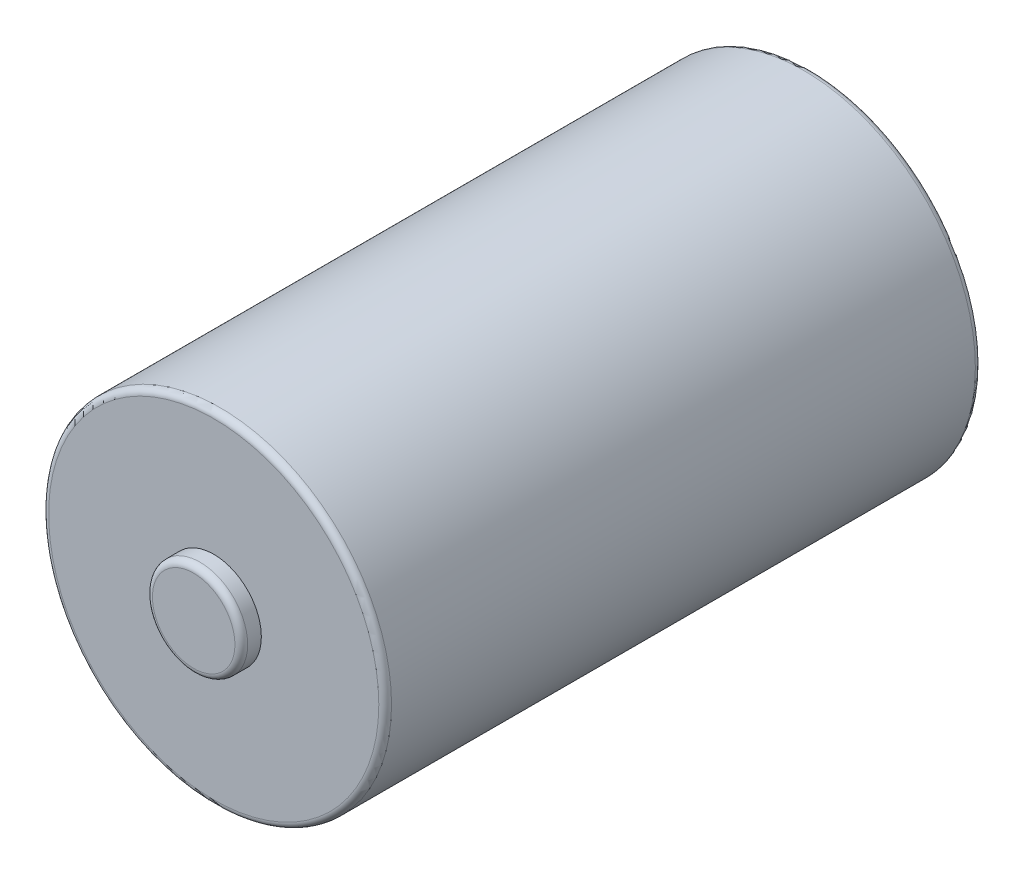
SolidWorks part; units mm, degrees
ref_plane "Front Plane" through (0, 0, 0) normal (0, 0, 1) x (1, 0, 0)
ref_plane "Top Plane" through (0, 0, 0) normal (0, 1, 0) x (1, 0, 0)
ref_plane "Right Plane" through (0, 0, 0) normal (1, 0, 0) x (0, 0, -1)
sketch "Sketch1" plane through (0, 0, 0) normal (0, 0, 1) x (1, 0, 0)
  circle A0 centre (0, 0) radius 17.1
extrude "Boss-Extrude1" add sketch "Sketch1" along normal blind 59.5
sketch "Sketch2" plane through (0, 0, 59.5) normal (0, 0, 1) x (1, 0, 0)
  circle A0 centre (0, 0) radius 4.75
extrude "Boss-Extrude2" add sketch "Sketch2" along normal blind 2
fillet "Fillet1" radius 0.635 2 edges at (17.1, 0, 59.5) (4.75, 0, 61.5)
fillet "Fillet2" radius 0.635 1 edges at (17.1, 0, 0)
